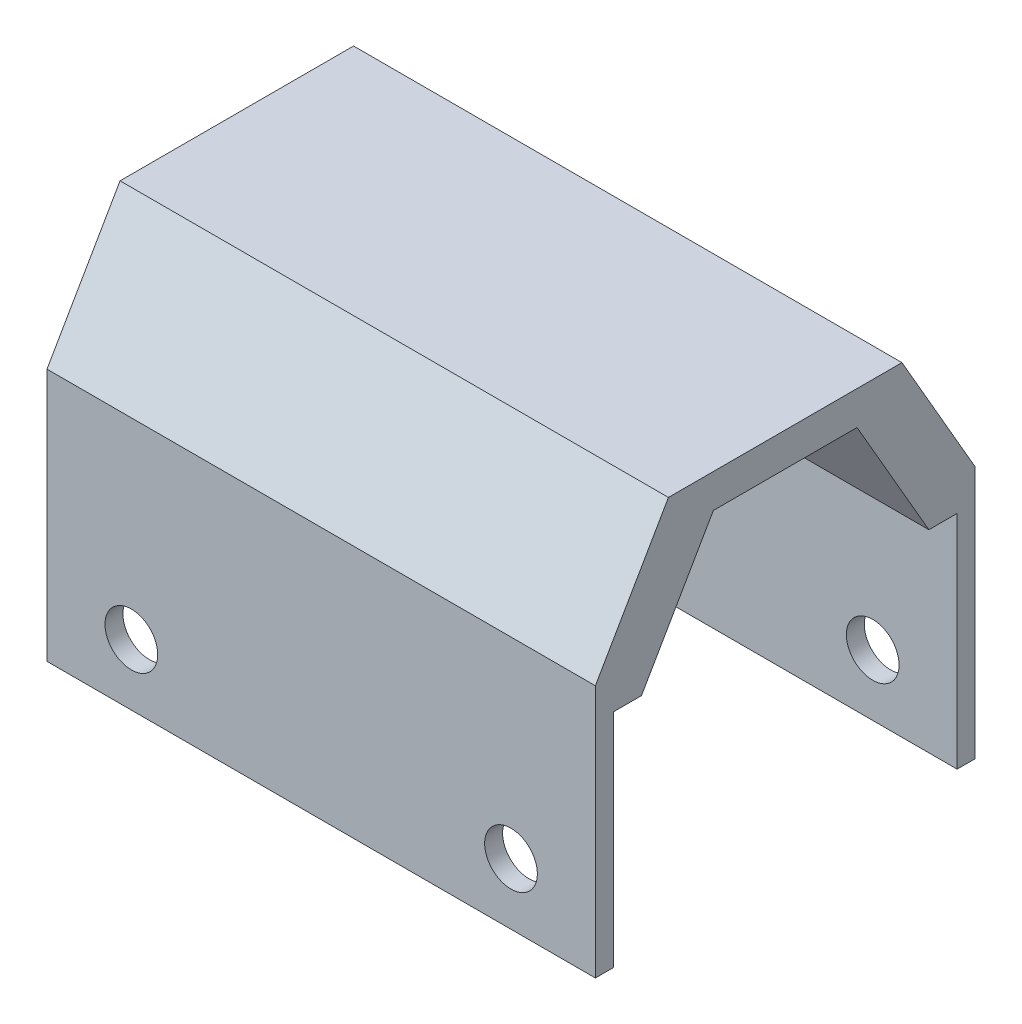
SolidWorks part; units mm, degrees
ref_plane "Plano frontal" through (0, 0, 0) normal (0, 0, 1) x (1, 0, 0)
ref_plane "Plano superior" through (0, 0, 0) normal (0, 1, 0) x (1, 0, 0)
ref_plane "Plano direito" through (0, 0, 0) normal (1, 0, 0) x (0, 0, -1)
sketch "Esboço1" plane through (0, 0, 0) normal (0, 0, 1) x (1, 0, 0)
  line L1 (-13, -9) -> (13, -9)
  line L2 (-13, -9) -> (-13, 9)
  line L3 (-13, 9) -> (13, 9)
  line L4 (13, -9) -> (13, 9)
  line L5 (-13, -9) -> (13, 9) construction
  line L6 (-13, 9) -> (13, -9) construction
  point P0 (0, 0)
  dimension "D1" = 26
  dimension "D2" = 18
extrude "Ressalto-extrusão1" add sketch "Esboço1" along normal blind 18
sketch "Esboço2" plane through (13, 0, 0) normal (1, 0, 0) x (0, 0, -1)
  line L7 (-18, -9) -> (0, -9) construction
  line L8 (-17.15, -9) -> (-0.85, -9)
  line L9 (-17.15, -9) -> (-17.15, 1.5)
  line L11 (-0.85, -9) -> (-0.85, 1.5)
  line L12 (-18, -9) -> (-18, 9) construction
  line L13 (0, -9) -> (0, 9) construction
  line L16 (-2.1873, 1.5) -> (-5.5936, 7.4)
  line L17 (-5.5936, 7.4) -> (-12.4064, 7.4)
  line L18 (-12.4064, 7.4) -> (-15.8127, 1.5)
  line L22 (-17.15, 1.5) -> (-15.8127, 1.5)
  line L23 (-2.1873, 1.5) -> (-0.85, 1.5)
  line L24 (-12.4064, -4.4) -> (-9, -4.4) [skipped]
  line L25 (-15.8127, 1.5) -> (-14.1095, -1.45) [skipped]
  line L26 (-3.6739, -1.075) -> (-1.9708, 1.875) [skipped]
  circle A0 centre (-9, 1.5) radius 5.9 construction
  point P22 (-9, -9)
  dimension "D1" = 11.8
  dimension "D2" = 10.5
  dimension "D5" = 0
  dimension "D3" = 0.85
  dimension "D4" = 0.85
extrude "Corte-extrusão1" cut sketch "Esboço2" against normal through all
sketch "Esboço3" plane through (0, 0, 18) normal (0, 0, 1) x (1, 0, 0)
  line L0 (13, -9) -> (13, 9) construction
  line L1 (-13, 9) -> (-13, -9) construction
  line L2 (-13, -9) -> (13, -9) construction
  circle A0 centre (-9, -6.1) radius 1.25
  circle A1 centre (9, -6.1) radius 1.25
  dimension "D1" = 2.5
  dimension "D2" = 2.5
  dimension "D3" = 4
  dimension "D4" = 4
  dimension "D5" = 2.9
  dimension "D6" = 2.9
extrude "Corte-extrusão2" cut sketch "Esboço3" against normal through all
chamfer "Chanfro1" distance 6 angle 30 2 edges at (0, 9, 18) (0, 9, 0)
